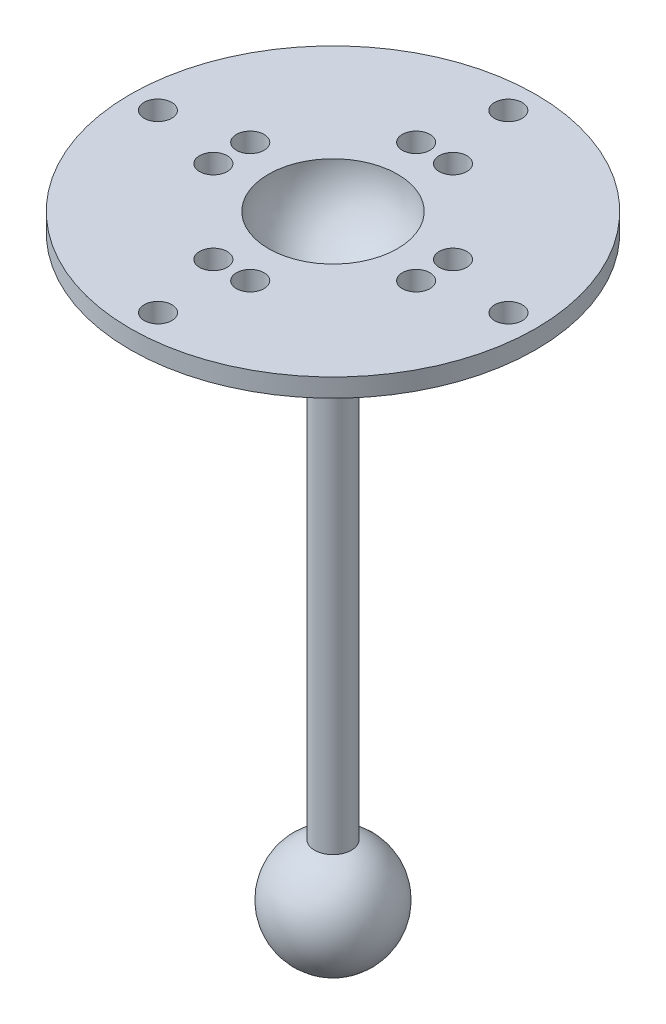
SolidWorks part; units mm, degrees
ref_plane "Front Plane" through (0, 0, 0) normal (0, 0, 1) x (1, 0, 0)
ref_plane "Top Plane" through (0, 0, 0) normal (0, 1, 0) x (1, 0, 0)
ref_plane "Right Plane" through (0, 0, 0) normal (1, 0, 0) x (0, 0, -1)
sketch "Sketch1" plane through (0, 0, 0) normal (1, 0, 0) x (0, 0, -1)
  line L0 (0, 4) -> (0, 0) construction
  line L1 (0, 0) -> (0, -25.34)
  line L2 (0, -25.34) -> (0, -28.34) construction
  line L3 (-4, 4) -> (-11, 4)
  line L4 (-11, 4) -> (-11, 3)
  line L5 (-11, 3) -> (-3.5092, 2.0802)
  line L6 (-4, 4) -> (-3.5, 4)
  line L7 (0, 0.127) -> (-1, 0.127) construction
  line L8 (1, 0.127) -> (1, -25.5116) construction
  line L9 (0, -25.5116) -> (-1, -25.5116) construction
  line L10 (-1, 0.127) -> (-1, -25.5116)
  line L11 (0, -31.34) -> (0, -25.34)
  line L12 (0, 0.5) -> (0, 0)
  line L13 (1, 0.127) -> (0, 0.127) construction
  line L14 (1, -25.5116) -> (0, -25.5116) construction
  line L15 (0, 10.6343) -> (0, 14.716) construction
  arc A0 (-1, -25.5116) -> (0, -31.34) centre (0, -28.34) ccw
  arc A1 (-3.5092, 2.0802) -> (-1, 0.127) centre (0, 4) ccw
  arc A2 (-3.5, 4) -> (0, 0.5) centre (0, 4) ccw
  arc A3 (0, 0) -> (1, 0.127) centre (0, 4) ccw construction
  arc A4 (0, 0.5) -> (-3.5, 4) centre (0, 4) ccw construction
  circle A5 centre (0, 4) radius 3.5 construction
  arc A6 (1, 0.127) -> (-4, 4) centre (0, 4) ccw construction
  circle A7 centre (0, 4) radius 4 construction
  arc A8 (-1, 0.127) -> (0, 0) centre (0, 4) ccw construction
  arc A9 (0, -31.34) -> (1, -25.5116) centre (0, -28.34) ccw construction
  arc A10 (1, -25.5116) -> (0, -25.34) centre (0, -28.34) ccw construction
  arc A11 (-4, 4) -> (-3.5092, 2.0802) centre (0, 4) ccw construction
  arc A12 (0, -25.34) -> (-1, -25.5116) centre (0, -28.34) ccw construction
  point P11 (3.8252, 5.1695)
  point P18 (0, -28.34)
  point P20 (3.5, 4)
  dimension "D1" = 25.34
  dimension "D2" = 4
  dimension "D3" = 3
  dimension "D5" = 7
  dimension "D6" = 1
  dimension "D7" = 97
  dimension "D8" = 2
  dimension "D4" = 0.5
revolve "Revolve1" add sketch "Sketch1" angle 360 about L15
sketch "Sketch2" plane through (0, 4, 0) normal (0, 1, 0) x (1, 0, 0)
  line L0 (-11, 0) -> (11, 0) construction
  line L1 (0.0096, 11) -> (0.0097, -11) construction
  circle A0 centre (0, 0) radius 0.5
  circle A1 centre (-9.5, 0) radius 0.75
  circle A2 centre (1.0096, -5.5) radius 0.75
  circle A3 centre (0.0097, -9.5) radius 0.75
  circle A4 centre (0.0097, 9.5) radius 0.75
  circle A5 centre (9.5193, 0) radius 0.75
  circle A6 centre (-5.4899, 1) radius 0.75
  circle A7 centre (-5.4899, -1) radius 0.75
  circle A8 centre (-0.9904, -5.5) radius 0.75
  circle A9 centre (5.5091, -1) radius 0.75
  circle A10 centre (5.5091, 1) radius 0.75
  circle A11 centre (1.0096, 5.5) radius 0.75
  circle A12 centre (-0.9904, 5.5) radius 0.75
  circle A13 centre (0, 0) radius 11 construction
  dimension "D1" = 1
  dimension "D3" = 1.5
  dimension "D6" = 1.5
  dimension "D9" = 1.5
  dimension "D2" = 9.5
  dimension "D4" = 5.5
  dimension "D5" = 9.5
  dimension "D7" = 1
  dimension "D8" = 5.4995
  dimension "D10" = 1
extrude "Cut-Extrude1" cut sketch "Sketch2" against normal blind 40 contours A7 | A1 | A3 | A8 | A2 | A9 | A10 | A5 | A11 | A12 | A4 | A0 | A6
